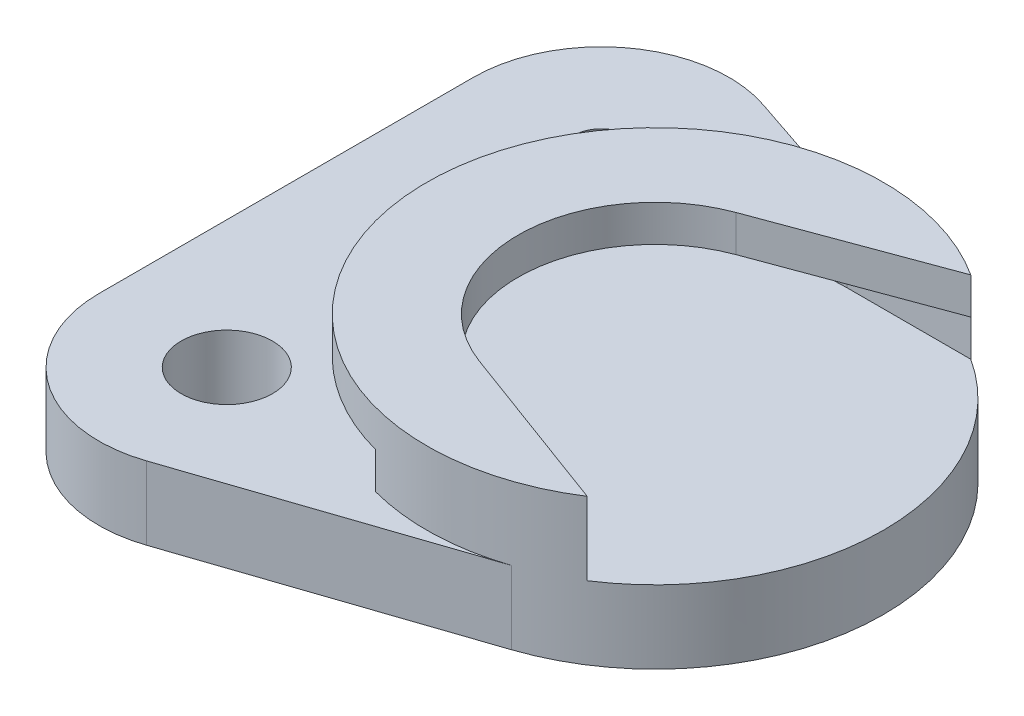
SolidWorks part; units mm, degrees
ref_plane "Спереди" through (0, 0, 0) normal (0, 0, 1) x (1, 0, 0)
ref_plane "Сверху" through (0, 0, 0) normal (0, 1, 0) x (1, 0, 0)
ref_plane "Справа" through (0, 0, 0) normal (1, 0, 0) x (0, 0, -1)
sketch "Эскиз1" plane through (0, 0, 0) normal (0, 1, 0) x (1, 0, 0)
  circle A0 centre (0, 0) radius 10.5 construction
  circle A1 centre (0, 0) radius 12.5
  dimension "D1" = 21
  dimension "D2" = 25
extrude "Бобышка-Вытянуть1" add sketch "Эскиз1" along normal blind 2
sketch "Эскиз2" plane through (0, 2, 0) normal (0, 1, 0) x (1, 0, 0)
  line L0 (0, -10.5) -> (6.7823, -10.5)
  line L1 (0, 10.5) -> (6.7823, 10.5)
  line L2 (-2.7176, 10.1422) -> (-3.2352, 12.0741)
  line L3 (-9.5162, 4.4375) -> (-11.3288, 5.2827)
  line L4 (0, 0) -> (-12.5, 0) construction
  line L5 (-9.5162, -4.4375) -> (-11.3288, -5.2827)
  line L6 (-2.7176, -10.1422) -> (-3.2352, -12.0741)
  arc A0 (0, 10.5) -> (-2.7176, 10.1422) centre (0, 0) ccw
  circle A1 centre (0, 0) radius 12.5 construction
  arc A2 (-11.3288, 5.2827) -> (6.7823, -10.5) centre (0, 0) ccw
  arc A3 (-2.7176, -10.1422) -> (0, -10.5) centre (0, 0) ccw
  arc A4 (-9.5162, 4.4375) -> (-9.5162, -4.4375) centre (0, 0) ccw
  arc A5 (6.7823, 10.5) -> (-3.2352, 12.0741) centre (0, 0) ccw
  circle M8 centre (0, 0) radius 12.5
  dimension "D1" = 21
  dimension "D2" = 25
  dimension "D3" = 75
  dimension "D4" = 25
  dimension "D5" = 75
  dimension "D6" = 2
  dimension "D7" = 2
  dimension "D8" = 2
  dimension "D9" = 2
extrude "Бобышка-Вытянуть2" add sketch "Эскиз2" along normal blind 2 contours L4 A4 L3 M8 | A4 L4 A2 L5 | A3 L6 L0 M8 | A0 L1 L2 M8
sketch "Эскиз4" plane through (0, 4, 0) normal (0, 1, 0) x (1, 0, 0)
  line L0 (6.7823, -10.5) -> (-2.5984, -7.0355)
  line L1 (6.7823, 10.5) -> (-2.5984, 7.0355)
  circle A0 centre (0, 0) radius 12.5
  arc A1 (-2.5984, 7.0355) -> (-2.5984, -7.0355) centre (0, 0) ccw
  arc M5 (-11.3288, 5.2827) -> (-11.3288, -5.2827) centre (0, 0) ccw
  line M6 (-11.3288, -5.2827) -> (-9.5162, -4.4375)
  arc M7 (-9.5162, -4.4375) -> (-9.5162, 4.4375) centre (0, 0) cw
  line M8 (-9.5162, 4.4375) -> (-11.3288, 5.2827)
  dimension "D1" = 15
extrude "Бобышка-Вытянуть3" add sketch "Эскиз4" along normal blind 2 contours A1 L1 A0 L0 M8 M7 M6 | M8 M5 M6 M7
ref_plane "Плоскость1" through (0, 0, 5) normal (0, 0, 1) x (1, 0, 0)
sketch "Эскиз5" plane through (0, 0, 0) normal (0, -1, 0) x (1, 0, 0)
  line L3 (-20.2, 10.25) -> (-20.2, -10.25)
  line L4 (-10.9655, 16.8838) -> (3.9903, 11.846)
  line L5 (3.9903, -11.846) -> (-10.9655, -16.8838)
  circle A0 centre (-13.2, 10.25) radius 2.5
  circle A1 centre (-13.2, -10.25) radius 1.5
  circle A2 centre (0, 0) radius 12.5 construction
  arc A6 (-10.9655, 16.8838) -> (-20.2, 10.25) centre (-13.2, 10.25) ccw
  arc A7 (-20.2, -10.25) -> (-10.9655, -16.8838) centre (-13.2, -10.25) ccw
  arc A8 (3.9903, -11.846) -> (3.9903, 11.846) centre (0, 0) ccw
  point P14 (-21.2, -20)
  point P17 (-21.2, 20)
  dimension "D1" = 5
  dimension "D2" = 3
  dimension "D10" = 14
  dimension "D3" = 13.2
  dimension "D4" = 13.2
  dimension "D5" = 10.25
  dimension "D6" = 10.25
  dimension "D7" = 40
  dimension "D8" = 20
extrude "Бобышка-Вытянуть4" add sketch "Эскиз5" against normal blind 2
sketch "Эскиз6" plane through (0, 0, 0) normal (0, -1, 0) x (1, 0, 0)
  line L3 (3.9903, 11.846) -> (-10.9655, 16.8838)
  line L4 (3.9903, 11.846) -> (-10.9655, 16.8838)
  line L5 (-20.2, 10.25) -> (-20.2, -10.25)
  line L9 (-20.2, 10.25) -> (-20.2, -10.25)
  line L10 (-10.9655, -16.8838) -> (3.9903, -11.846)
  line L11 (-10.9655, -16.8838) -> (3.9903, -11.846)
  circle A0 centre (-13.2, -10.25) radius 1.5 construction
  circle A1 centre (-13.2, -10.25) radius 1.5
  arc A3 (3.9903, -11.846) -> (3.9903, 11.846) centre (0, 0) ccw
  arc A4 (-10.9655, 16.8838) -> (-20.2, 10.25) centre (-13.2, 10.25) ccw
  arc A5 (-10.9655, 16.8838) -> (-20.2, 10.25) centre (-13.2, 10.25) ccw
  arc A6 (3.9903, -11.846) -> (3.9903, 11.846) centre (0, 0) ccw
  circle A13 centre (-13.2, 10.25) radius 5 construction
  circle A14 centre (-8.2, 10.25) radius 1
  circle A15 centre (-13.2, 5.25) radius 1
  circle A16 centre (-18.2, 10.25) radius 1
  circle A17 centre (-13.2, 15.25) radius 1
  circle A18 centre (-13.2, 10.25) radius 2.5 construction
  circle A19 centre (-13.2, 10.25) radius 2.5
  arc A23 (-20.2, -10.25) -> (-10.9655, -16.8838) centre (-13.2, -10.25) ccw
  arc A24 (-20.2, -10.25) -> (-10.9655, -16.8838) centre (-13.2, -10.25) ccw
  dimension "D2" = 2
  dimension "D3" = 2
  dimension "D1" = 0
extrude "Бобышка-Вытянуть5" add sketch "Эскиз6" along normal blind 2
